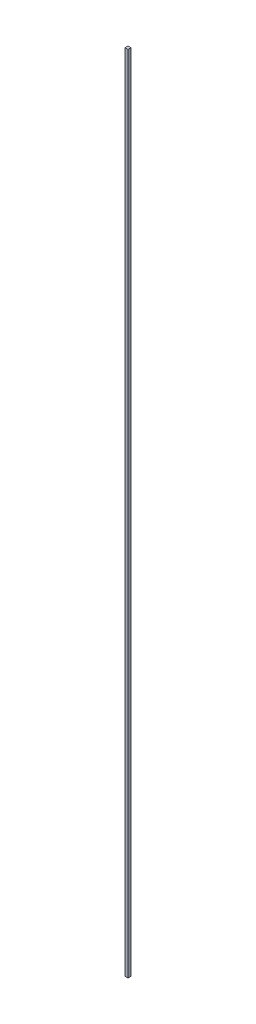
SolidWorks part; units mm, degrees
ref_plane "Front Plane" through (0, 0, 0) normal (0, 0, 1) x (1, 0, 0)
ref_plane "Top Plane" through (0, 0, 0) normal (0, 1, 0) x (1, 0, 0)
ref_plane "Right Plane" through (0, 0, 0) normal (1, 0, 0) x (0, 0, -1)
sketch "Sketch1" plane through (0, 0, 0) normal (0, 1, 0) x (1, 0, 0)
  line L1 (0, 0) -> (2, 0)
  line L2 (0, 0) -> (0, 2)
  line L3 (0, 2) -> (2, 2)
  line L4 (2, 0) -> (2, 2)
extrude "Boss-Extrude1" add sketch "Sketch1" along normal blind 541.9 flip side to cut
